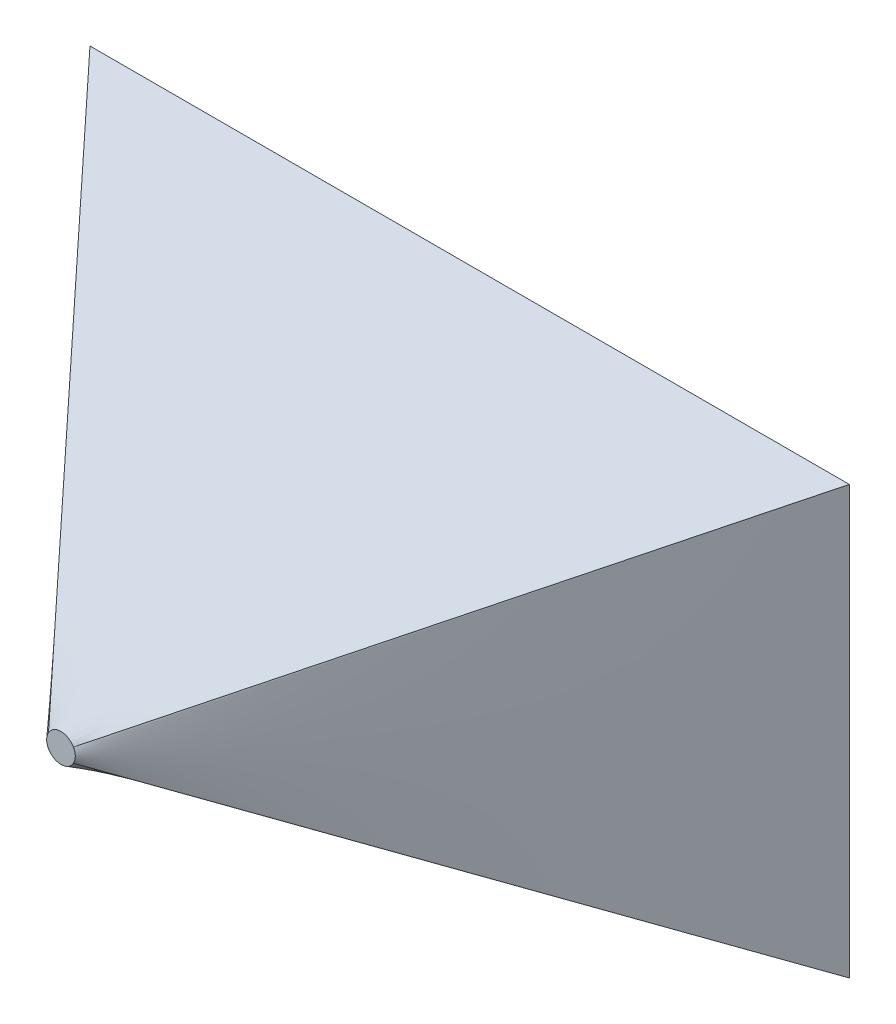
SolidWorks part; units mm, degrees
ref_plane "Alzado" through (0, 0, 0) normal (0, 0, 1) x (1, 0, 0)
ref_plane "Planta" through (0, 0, 0) normal (0, 1, 0) x (1, 0, 0)
ref_plane "Vista lateral" through (0, 0, 0) normal (1, 0, 0) x (0, 0, -1)
sketch "Croquis1" plane through (0, 0, 0) normal (0, 0, 1) x (1, 0, 0)
  line L5 (-185.8, 104.6) -> (185.8, 104.6)
  line L6 (-185.8, 104.6) -> (-185.8, -104.6)
  line L7 (-185.8, -104.6) -> (185.8, -104.6)
  line L8 (185.8, 104.6) -> (185.8, -104.6)
  line L9 (-185.8, 104.6) -> (185.8, -104.6) construction
  line L10 (-185.8, -104.6) -> (185.8, 104.6) construction
  point P0 (0, 0)
  dimension "D1" = 371.6
  dimension "D2" = 209.2
ref_plane "Plano2" through (0, 0, 0) normal (0, 0, 1) x (1, 0, 0)
ref_plane "Plano3" through (0, 0, 200) normal (0, 0, 1) x (1, 0, 0)
sketch "Croquis2" plane through (0, 0, 200) normal (0, 0, 1) x (1, 0, 0)
  circle A0 centre (0, 0) radius 7
loft "Recubrir2" add profiles "Croquis2", "Croquis1"
